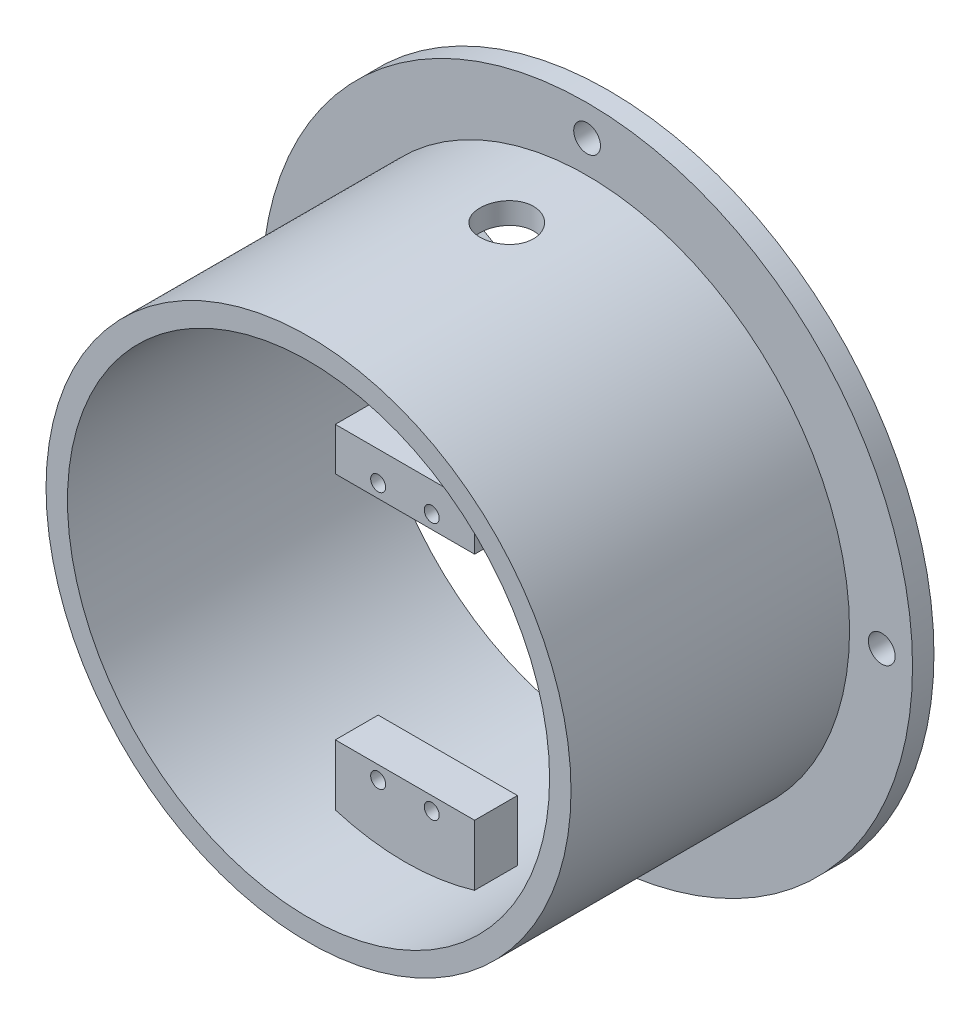
SolidWorks part; units mm, degrees
ref_plane "Front Plane" through (0, 0, 0) normal (1, 0, 0) x (0, 1, 0)
ref_plane "Top Plane" through (0, 0, 0) normal (0, 0, 1) x (0, 1, 0)
ref_plane "Right Plane" through (0, 0, 0) normal (0, 1, 0) x (-1, 0, 0)
sketch "Sketch2" plane through (0, 0, 0) normal (0, 0, 1) x (0, 1, 0)
  circle A0 centre (0, 0) radius 45
  circle A1 centre (0, 0) radius 60.75
  dimension "D1" = 90
  dimension "D2" = 121.5
extrude "Boss-Extrude1" add sketch "Sketch2" along normal blind 4
sketch "Sketch3" plane through (0, 0, 4) normal (0, 0, 1) x (1, 0, 0)
  circle A5 centre (0, 0) radius 49
  circle A6 centre (0, 0) radius 49
  circle A9 centre (0, 0) radius 45
  circle A10 centre (0, 0) radius 45
  dimension "D1" = 4
  dimension "D2" = 0
extrude "Boss-Extrude2" add sketch "Sketch3" along normal blind 52
sketch "Sketch4" plane through (0, 0, 0) normal (1, 0, 0) x (0, 1, 0)
  line L0 (0, 0) -> (0, 56) construction
  line L1 (49, 56) -> (-49, 56) construction
  line L2 (-60.75, 0) -> (60.75, 0) construction
  line L3 (11.25, 0) -> (19.25, 0)
  line L4 (11.25, 0) -> (11.25, 38)
  line L5 (11.25, 38) -> (19.25, 38)
  line L6 (19.25, 0) -> (19.25, 38)
  line L7 (45, 56) -> (-45, 56) construction
  line L8 (-49, 56) -> (-49, 4) construction
  line L9 (-46.75, 38) -> (-31.75, 38)
  line L10 (-46.75, 38) -> (-46.75, 30)
  line L11 (-46.75, 30) -> (-31.75, 30)
  line L12 (-31.75, 38) -> (-31.75, 30)
  dimension "D1" = 8
  dimension "D2" = 11.25
  dimension "D3" = 18
  dimension "D4" = 2.25
  dimension "D5" = 18
  dimension "D6" = 8
  dimension "D7" = 15
extrude "Boss-Extrude3" add sketch "Sketch4" along normal mid plane 26
sketch "Sketch5" plane through (0, 11.25, 0) normal (0, -1, 0) x (1, 0, 0)
  line L0 (0, 38) -> (0, 0) construction
  line L1 (13, 38) -> (-13, 38) construction
  line L2 (13, 0) -> (-13, 0) construction
  line L3 (5, 5) -> (-5, 5)
  line L4 (5, 5) -> (5, 28)
  line L5 (5, 28) -> (-5, 28)
  line L6 (-5, 5) -> (-5, 28)
  line L7 (5, 5) -> (-5, 28) construction
  line L8 (5, 28) -> (-5, 5) construction
  point P5 (0, 16.5)
  dimension "D1" = 5
  dimension "D2" = 10
  dimension "D3" = 10
extrude "Cut-Extrude1" cut sketch "Sketch5" against normal up to next (8 mm away)
sketch "Sketch7" plane through (0, 11.25, 0) normal (0, -1, 0) x (1, 0, 0)
  line L0 (0, 28) -> (0, 5) construction
  line L1 (5, 28) -> (-5, 28) construction
  line L2 (-5, 5) -> (5, 5) construction
  circle A0 centre (0, 19) radius 5
  dimension "D1" = 10
  dimension "D2" = 14
extrude "Cut-Extrude2" cut sketch "Sketch7" against normal through all
sketch "Sketch8" plane through (0, 0, 38) normal (0, 0, 1) x (1, 0, 0)
  line L0 (-13, -34.25) -> (13, -34.25) construction
  line L1 (-13, -31.75) -> (-13, -43.0813) construction
  line L2 (13, -31.75) -> (13, -43.0813) construction
  line L3 (13, -31.75) -> (-13, -31.75) construction
  line L4 (0, -34.25) -> (0, 13.75) construction
  line L5 (-13, 13.75) -> (13, 13.75) construction
  line L6 (13, 19.25) -> (13, 11.25) construction
  circle A0 centre (5, -34.25) radius 1.4
  circle A1 centre (5, 13.75) radius 1.4
  circle A2 centre (-5, 13.75) radius 1.4
  circle A3 centre (-5, -34.25) radius 1.4
  point P16 (0, 13.75)
  dimension "D3" = 2.8
  dimension "D5" = 5
  dimension "D1" = 2.5
  dimension "D2" = 48
  dimension "D4" = 5
extrude "Cut-Extrude5" cut sketch "Sketch8" against normal blind 7.2
sketch "Sketch9" plane through (0, 0, 0) normal (0, 0, -1) x (1, 0, 0)
  line L0 (0, -11.25) -> (0, -45) construction
  line L1 (13, -11.25) -> (-13, -11.25) construction
  line L2 (13, -11.25) -> (-13, -11.25)
  line L3 (-13, -11.25) -> (-37.2484, -25.2498)
  line L4 (13, -11.25) -> (37.2484, -25.2498)
  line L5 (19.5167, -24.25) -> (24.9065, -27.3618)
  line L7 (-19.5167, -24.25) -> (-24.9065, -27.3618)
  line L8 (19.5167, -24.25) -> (-19.5167, -24.25)
  line L9 (10.8564, -19.25) -> (24.9065, -27.3618) construction
  line L10 (10.8564, -19.25) -> (-10.8564, -19.25) construction
  line L11 (-10.8564, -19.25) -> (-24.9065, -27.3618) construction
  line L12 (13, -19.25) -> (-13, -19.25) construction
  circle A0 centre (0, 0) radius 45 construction
  arc A1 (-37.2484, -25.2498) -> (37.2484, -25.2498) centre (0, 0) ccw
  arc A2 (-24.9065, -27.3618) -> (24.9065, -27.3618) centre (0, 0) ccw
  dimension "D1" = 60
  dimension "D3" = 5
  dimension "D2" = 8
extrude "Boss-Extrude4" add sketch "Sketch9" against normal blind 4
sketch "Sketch10" plane through (0, 0, 4) normal (0, 0, 1) x (1, 0, 0)
  circle A2 centre (0, 0) radius 55 construction
  circle A3 centre (-55, 0) radius 2.5
  circle A4 centre (0, 55) radius 2.5
  circle A5 centre (0, 0) radius 55 construction
  circle A6 centre (55, 0) radius 2.5
  circle A7 centre (0, 0) radius 55 construction
  circle A8 centre (0, -55) radius 2.5
  circle A9 centre (0, 0) radius 55 construction
  point P18 (0, 0)
  dimension "D1" = 110
  dimension "D2" = 5
  dimension "D3" = 4
extrude "Cut-Extrude6" cut sketch "Sketch10" against normal through all
